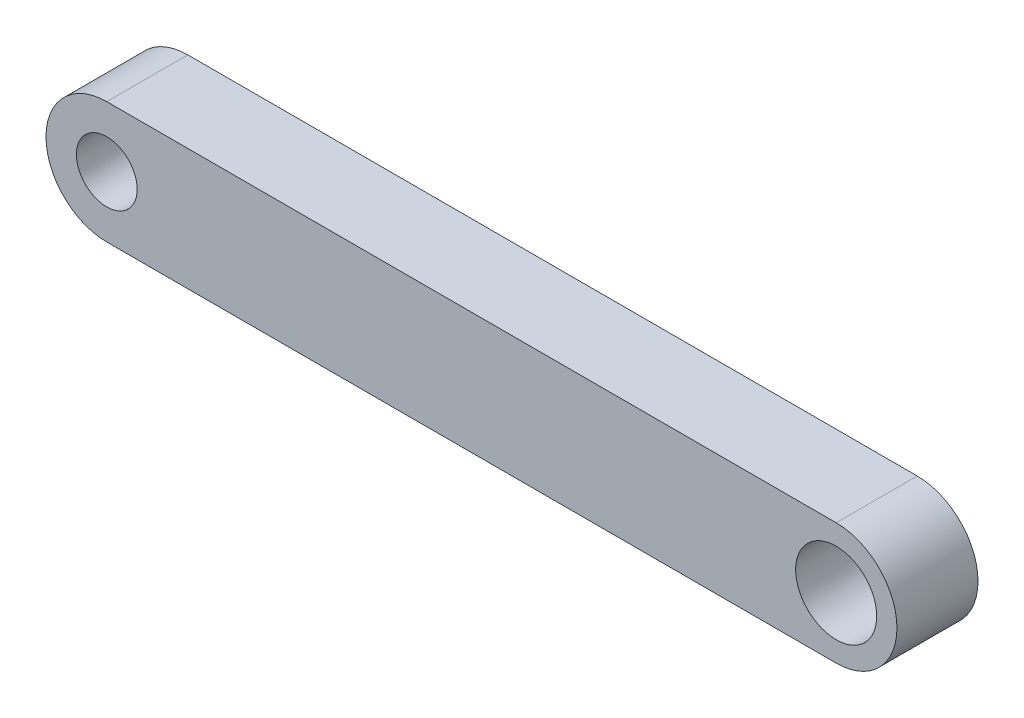
SolidWorks part; units mm, degrees
ref_plane "Front Plane" through (0, 0, 0) normal (0, 0, 1) x (1, 0, 0)
ref_plane "Top Plane" through (0, 0, 0) normal (0, 1, 0) x (1, 0, 0)
ref_plane "Right Plane" through (0, 0, 0) normal (1, 0, 0) x (0, 0, -1)
sketch "Sketch1" plane through (0, 0, 0) normal (0, 0, 1) x (1, 0, 0)
  line L0 (0, 3) -> (-36, 3)
  line L1 (0, -3) -> (-36, -3)
  line L2 (-18, -3) -> (-18, 3) construction
  line L3 (0, 3) -> (0, -3) construction
  line L4 (-36, 3) -> (-36, -3) construction
  circle A0 centre (0, 0) radius 2
  arc A1 (0, -3) -> (0, 3) centre (0, 0) ccw
  arc A2 (-36, -3) -> (-36, 3) centre (-36, 0) cw
  circle A4 centre (-36, 0) radius 1.5
  dimension "D1" = 4
  dimension "D2" = 6
  dimension "D4" = 3
  dimension "D3" = 36
extrude "Boss-Extrude1" add sketch "Sketch1" along normal blind 4
